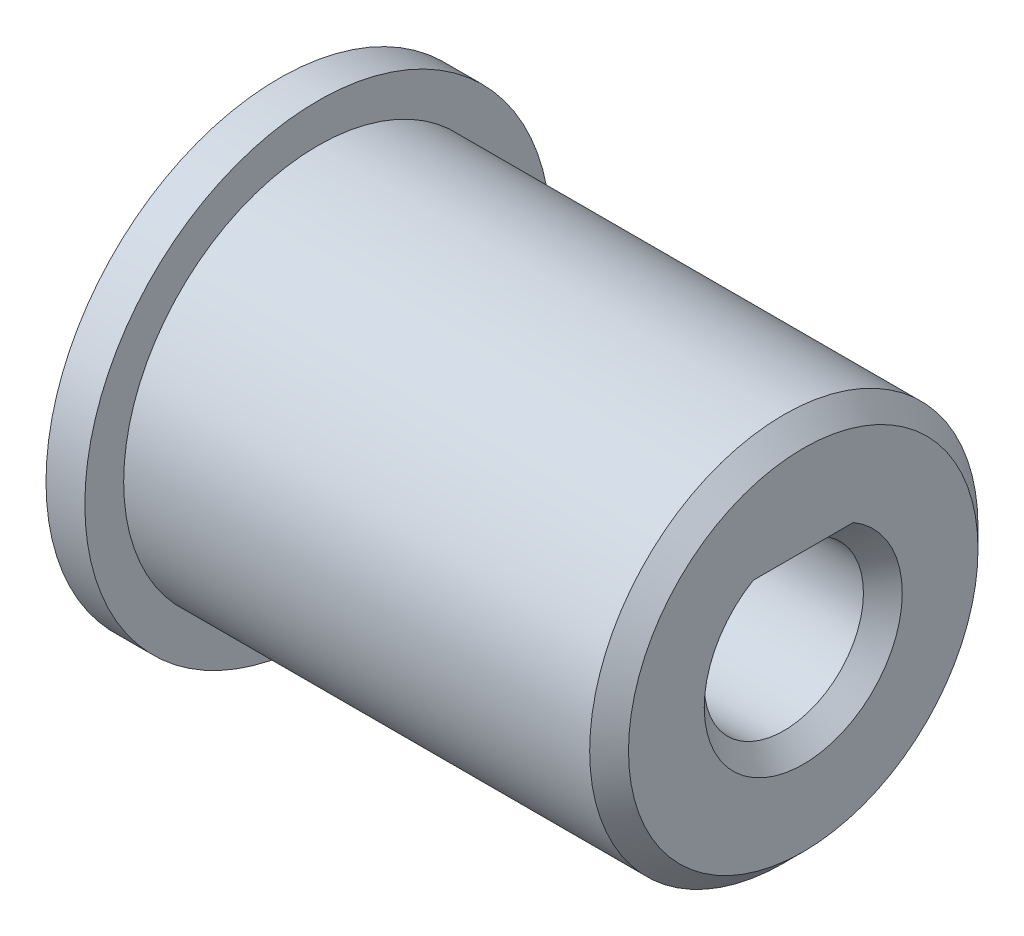
SolidWorks part; units mm, degrees
ref_plane "Ebene vorne" through (0, 0, 0) normal (0, 0, 1) x (1, 0, 0)
ref_plane "Ebene oben" through (0, 0, 0) normal (0, 1, 0) x (1, 0, 0)
ref_plane "Ebene rechts" through (0, 0, 0) normal (1, 0, 0) x (0, 0, -1)
sketch "Skizze2" plane through (0, 0, 0) normal (1, 0, 0) x (0, 0, -1)
  circle A0 centre (0, 0) radius 10
  dimension "D1" = 20
extrude "Aufsatz-Linear austragen1" add sketch "Skizze2" along normal blind 25
sketch "Skizze3" plane through (0, 0, 0) normal (-1, 0, 0) x (0, 0, 1)
  circle A0 centre (0, 0) radius 12
  dimension "D1" = 24
extrude "Aufsatz-Linear austragen2" add sketch "Skizze3" along normal blind 2
sketch "Skizze4" plane through (25, 0, 0) normal (1, 0, 0) x (0, 0, -1)
  line L0 (-2.2913, 3.4) -> (2.2913, 3.4)
  line L1 (-6.4521, 0) -> (8.6873, 0) construction
  arc A0 (-2.2913, 3.4) -> (2.2913, 3.4) centre (0, 0) ccw
  point P5 (0, -4.1)
  dimension "D1" = 4.1
  dimension "D2" = 7.5
extrude "Schnitt-Linear austragen1" cut sketch "Skizze4" against normal blind 15
chamfer "Fase1" distance 1 angle 45 2 edges at (25, 3.4, 0) (25, -4.1, 0)
chamfer "Fase2" distance 1 angle 45 1 edges at (25, 0, -10)
hole_wizard "Ø3.1 (3.1) Durchmesser Bohrung1" positions "Skizze5" profile "Skizze6" hole size "Ø3.1" standard "ISO"
sketch "Skizze5" plane through (-2, 0, 0) normal (-1, 0, 0) x (0, 0, 1)
  line L0 (0, 0) -> (-50000, 0) construction
  line L1 (0, 0) -> (0, -50000) construction
  point P5 (-4.25, 0)
  point P7 (4.25, 0)
  point P15 (0, 0)
  point P16 (-4.25, 0)
  dimension "D1" = 8.5
sketch "Skizze6" plane through (-2, 0, 4.25) normal (0, 1, 0) x (0, 0, 1)
  line L0 (0, 0) -> (0, 7.9313)
  line L1 (0, 7.9313) -> (1.55, 7)
  line L2 (1.55, 7) -> (1.55, 0)
  line L5 (1.55, 0) -> (0, 0)
  line L10 (0, 7.9313) -> (-1.55, 7) construction
  line L11 (0, -6.35) -> (0, 107.95) construction
  dimension "Bohrerdurchmesser" = 3.1
  dimension "Bohrungstiefe" = 7
  dimension "Spitzenwinkel" = 118
chamfer "Fase3" distance 1 angle 45 2 edges at (-2, 0, 5.8) (-2, 0, -2.7)
